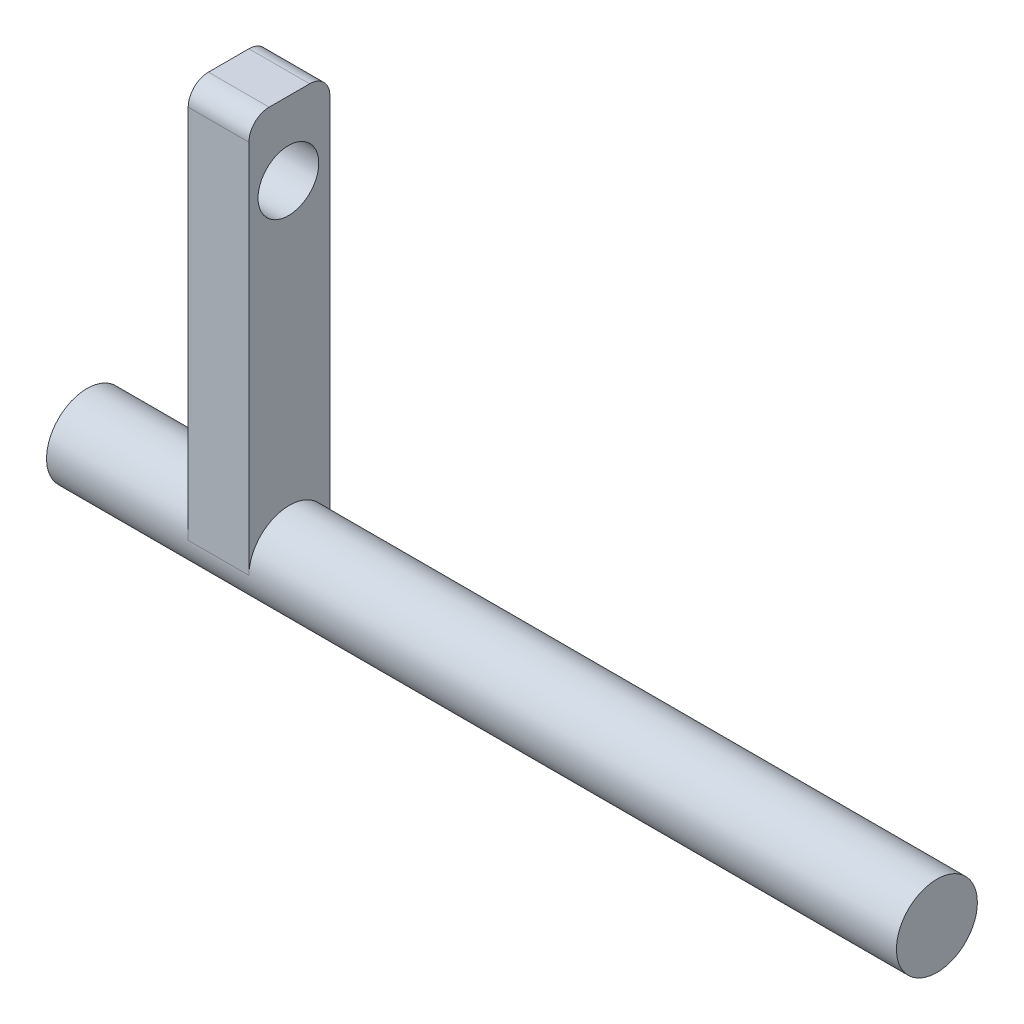
SolidWorks part; units mm, degrees
ref_plane "Front Plane" through (0, 0, 0) normal (0, 0, 1) x (1, 0, 0)
ref_plane "Top Plane" through (0, 0, 0) normal (0, 1, 0) x (1, 0, 0)
ref_plane "Right Plane" through (0, 0, 0) normal (1, 0, 0) x (0, 0, -1)
sketch "Sketch1" plane through (0, 0, 0) normal (1, 0, 0) x (0, 0, -1)
  circle A0 centre (-12.6585, 7.0005) radius 2
extrude "Boss-Extrude1" add sketch "Sketch1" along normal blind 42
sketch "Sketch2" plane through (0, 0, 0) normal (-1, 0, 0) x (0, 0, 1)
  line L0 (10.6585, 7.0005) -> (10.6585, 13.7605)
  line L1 (14.6585, 13.7605) -> (14.6585, 7.0005)
  circle A0 centre (12.6585, 7.0005) radius 2 construction
  arc A1 (10.6585, 13.7605) -> (14.6585, 13.7605) centre (12.6585, 13.7605) cw
  circle A3 centre (12.6585, 7.0005) radius 2
  arc A4 (10.6585, 7.0005) -> (14.6585, 7.0005) centre (12.6585, 7.0005) ccw
  dimension "D1" = 0
extrude "Boss-Extrude2" add sketch "Sketch2" against normal blind 10
sketch "Sketch3" plane through (0, 0, 0) normal (-1, 0, 0) x (0, 0, 1)
  line L0 (10.6585, 7.0005) -> (10.6585, 13.7605)
  line L1 (14.6585, 13.7605) -> (14.6585, 7.0005)
  arc A0 (14.6585, 7.0005) -> (10.6585, 7.0005) centre (12.6585, 7.0005) ccw
  arc A1 (10.6585, 7.0005) -> (14.6585, 7.0005) centre (12.6585, 7.0005) ccw construction
  arc A3 (14.6585, 13.7605) -> (10.6585, 13.7605) centre (12.6585, 13.7605) ccw construction
  arc A4 (14.6585, 13.7605) -> (10.6585, 13.7605) centre (12.6585, 13.7605) ccw
extrude "Cut-Extrude1" cut sketch "Sketch3" against normal blind 7
sketch "Sketch4" plane through (7, 0, 0) normal (-1, 0, 0) x (0, 0, 1)
  line L0 (10.6585, 7.0005) -> (10.6585, 13.7605)
  line L1 (10.6585, 13.7605) -> (10.6585, 36.0099)
  line L2 (14.6585, 36.0099) -> (14.6585, 7.0005)
  line L3 (10.6585, 36.0099) -> (14.6585, 36.0099)
  arc A0 (10.6585, 36.0099) -> (14.6585, 36.0099) centre (12.6585, 36.0099) cw
  arc M3 (14.6585, 13.7605) -> (10.6585, 13.7605) centre (12.6585, 13.7605) ccw
extrude "Boss-Extrude4" add sketch "Sketch4" against normal blind 3 contours L3 L1 L2 M3 | A0 L3
sketch "Sketch5" plane through (7, 0, 0) normal (-1, 0, 0) x (0, 0, 1)
  line L0 (10.6585, 22.9195) -> (14.6585, 22.9195) construction
  line L1 (10.6585, 36.0099) -> (10.6585, 7.0005) construction
  line L2 (14.6585, 7.0005) -> (14.6585, 36.0099) construction
  circle A0 centre (12.7066, 22.9195) radius 1.5
extrude "Cut-Extrude3" cut sketch "Sketch5" against normal through all contours A0
sketch "Sketch6" plane through (7, 0, 0) normal (-1, 0, 0) x (0, 0, 1)
  line L1 (18.5418, 38.6954) -> (6.7193, 38.6954)
  line L2 (18.5418, 38.6954) -> (18.5418, 26.5383)
  line L3 (18.5418, 26.5383) -> (6.7193, 26.5383)
  line L4 (6.7193, 38.6954) -> (6.7193, 26.5383)
extrude "Cut-Extrude5" cut sketch "Sketch6" against normal through all
fillet "Fillet4" radius 1 1 edges at (8.5, 26.5383, 14.6585)
fillet "Fillet5" radius 1 1 edges at (8.5, 26.5383, 10.6585)
